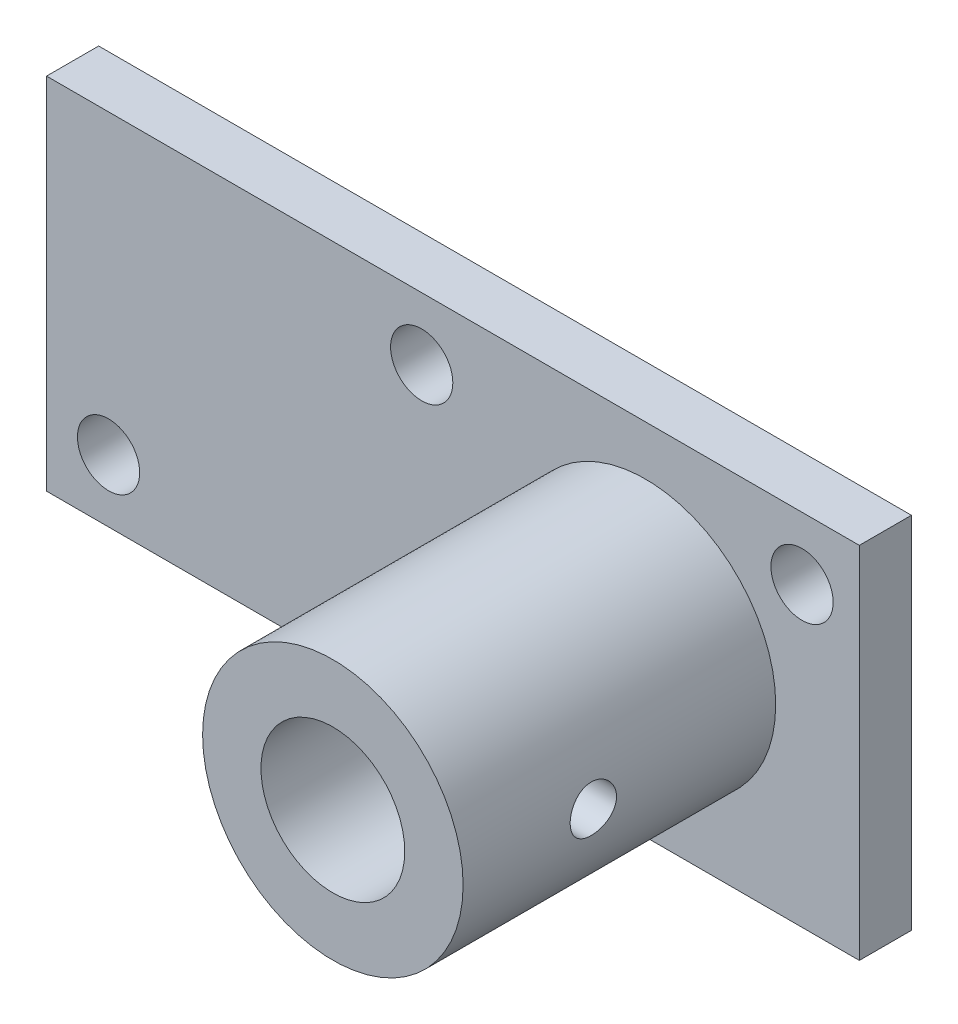
SolidWorks part; units mm, degrees
ref_plane "Front Plane" through (0, 0, 0) normal (0, 0, 1) x (1, 0, 0)
ref_plane "Top Plane" through (0, 0, 0) normal (0, 1, 0) x (1, 0, 0)
ref_plane "Right Plane" through (0, 0, 0) normal (1, 0, 0) x (0, 0, -1)
sketch "Sketch1" plane through (0, 0, 0) normal (0, 0, 1) x (1, 0, 0)
  line L1 (0, 0) -> (39.624, 0)
  line L2 (0, 0) -> (0, -17.526)
  line L3 (0, -17.526) -> (39.624, -17.526)
  line L4 (39.624, 0) -> (39.624, -17.526)
  dimension "D1" = 17.526
  dimension "1.55" = 39.624
extrude "Boss-Extrude1" add sketch "Sketch1" along normal blind 2.54
sketch "Sketch2" plane through (0, 0, 2.54) normal (0, 0, 1) x (1, 0, 0)
  line L0 (39.624, 0) -> (0, 0) construction
  line L1 (39.624, -17.526) -> (39.624, 0) construction
  line L2 (0, -17.526) -> (39.624, -17.526) construction
  circle A0 centre (36.83, -3.048) radius 1.5179
  circle A2 centre (21.5646, -14.478) radius 1.5179
  circle A3 centre (18.288, -3.048) radius 1.5179
  circle A4 centre (3.0226, -14.478) radius 1.5179
  dimension "D1" = 3.048
  dimension "D5" = 18.542
  dimension "D9" = 18.542
  dimension "D4" = 2.794
  dimension "D7" = 3.048
  dimension "D8" = 3.048
  dimension "D10" = 18.0594
extrude "Cut-Extrude1" cut sketch "Sketch2" against normal through all
sketch "Sketch3" plane through (0, 0, 2.54) normal (0, 0, 1) x (1, 0, 0)
  line L0 (3.0226, -14.478) -> (18.288, -3.048) construction
  line L1 (21.5646, -14.478) -> (36.83, -3.048) construction
  circle A0 centre (10.6553, -8.763) radius 6.35
  circle A1 centre (29.1973, -8.763) radius 6.35
  dimension "D1" = 12.7
  dimension ".5" = 12.7
extrude "Boss-Extrude2" add sketch "Sketch3" along normal blind 15.24 contours A1
sketch "Sketch5" plane through (0, 0, 17.78) normal (0, 0, 1) x (1, 0, 0)
  circle A0 centre (29.1973, -8.763) radius 3.5052
  circle A1 centre (29.1973, -8.763) radius 6.35 construction
  dimension "D1" = 7.0104
extrude "Cut-Extrude2" cut sketch "Sketch5" against normal through all
ref_plane "Plane1" through (35.5473, 0, 0) normal (1, 0, 0) x (0, 0, -1)
sketch "Sketch6" plane through (35.5473, 0, 0) normal (1, 0, 0) x (0, 0, -1)
  line L0 (-2.54, 0) -> (0, 0) construction
  line L1 (-17.78, -2.413) -> (-17.78, -15.113) construction
  circle A0 centre (-11.43, -8.763) radius 1.1303
  dimension "D1" = 2.2606
  dimension "D2" = 8.763
  dimension "D3" = 6.35
extrude "Cut-Extrude3" cut sketch "Sketch6" against normal up to next
sketch "Sketch7" plane through (0, 0, 0) normal (0, 0, -1) x (-1, 0, 0)
  line L0 (0, 0) -> (0, -17.526) construction
  line L1 (-39.624, -17.526) -> (-39.624, 0) construction
  line L2 (-39.624, 0) -> (0, 0) construction
  line L3 (0, -17.526) -> (-39.624, -17.526) construction
  circle A0 centre (-15.748, -14.224) radius 2.3813
  circle A1 centre (-5.715, -3.556) radius 2.3813
  circle A2 centre (-23.368, -3.556) radius 2.3813
  circle A3 centre (-33.274, -14.224) radius 2.3812
  dimension "D1" = 4.7625
  dimension "D2" = 15.748
  dimension "D3" = 5.715
  dimension "D4" = 16.256
  dimension "D5" = 6.35
  dimension "D6" = 14.224
  dimension "D7" = 14.224
  dimension "D8" = 13.97
  dimension "D9" = 13.97
extrude "Cut-Extrude4" cut sketch "Sketch7" against normal blind 1.27
